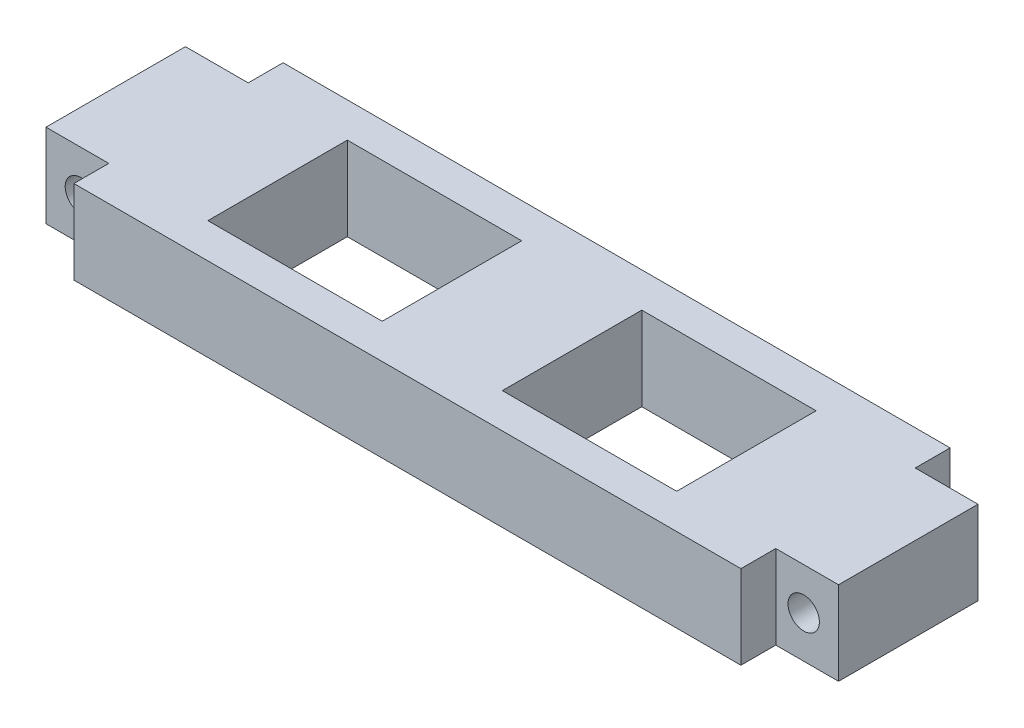
SolidWorks part; units mm, degrees
ref_plane "Front Plane" through (0, 0, 0) normal (0, 0, 1) x (1, 0, 0)
ref_plane "Top Plane" through (0, 0, 0) normal (0, 1, 0) x (1, 0, 0)
ref_plane "Right Plane" through (0, 0, 0) normal (1, 0, 0) x (0, 0, -1)
sketch "Sketch1" plane through (0, 0, 0) normal (0, 1, 0) x (1, 0, 0)
  line L0 (144.5, 0) -> (152.5, 0) construction
  line L1 (-55, 0) -> (55, 0) construction
  line L2 (-47.8333, 15) -> (47.8333, 15)
  line L3 (-47.8333, -15) -> (47.8333, -15)
  line L4 (47.8333, 10) -> (56.8333, 10)
  line L5 (47.8333, 15) -> (47.8333, 10)
  line L6 (-47.8333, 15) -> (-47.8333, 10)
  line L7 (-47.8333, 0) -> (47.8333, 0) construction
  line L8 (-47.8333, 10) -> (-56.8333, 10)
  line L9 (-56.8333, 10) -> (-56.8333, -10)
  line L10 (-56.8333, -10) -> (-47.8333, -10)
  line L11 (56.8333, 10) -> (56.8333, -10)
  line L12 (56.8333, -10) -> (47.8333, -10)
  line L13 (-47.8333, -10) -> (-47.8333, -15)
  line L14 (47.8333, -10) -> (47.8333, -15)
  line L15 (0, 31.4414) -> (0, -28.5732) construction
  line L16 (0, -55) -> (0, 55) construction
  line L18 (-33.6153, 10) -> (-8.6153, 10)
  line L19 (-33.6153, 10) -> (-33.6153, -10)
  line L20 (-33.6153, -10) -> (-8.6153, -10)
  line L21 (-8.6153, 10) -> (-8.6153, -10)
  line L22 (8.6153, 10) -> (33.6153, 10)
  line L23 (8.6153, 10) -> (8.6153, -10)
  line L24 (8.6153, -10) -> (33.6153, -10)
  line L25 (33.6153, 10) -> (33.6153, -10)
  point P5 (8.75, 0)
  dimension "D1" = 9
  dimension "D2" = 20
  dimension "D3" = 10
  dimension "D4" = 95.6667
  dimension "D5" = 9
  dimension "D6" = 20
  dimension "D7" = 10
  dimension "D8" = 20
  dimension "D9" = 20
  dimension "D10" = 10
  dimension "D11" = 10
  dimension "D12" = 25
  dimension "D13" = 25
  dimension "D14" = 5
  dimension "D15" = 30
extrude "Boss-Extrude1" add sketch "Sketch1" along normal blind 12
sketch "Sketch2" plane through (0, 0, -10) normal (0, 0, -1) x (-1, 0, 0)
  line L0 (-47.8333, 12) -> (-47.8333, 0) construction
  line L1 (-56.8333, 12) -> (-47.8333, 12) construction
  line L2 (0, 55) -> (0, -55) construction
  circle A0 centre (-51.8333, 6) radius 2.25
  circle A1 centre (51.8333, 6) radius 2.25
  dimension "D1" = 4
  dimension "D2" = 6
extrude "Cut-Extrude1" cut sketch "Sketch2" against normal through all
